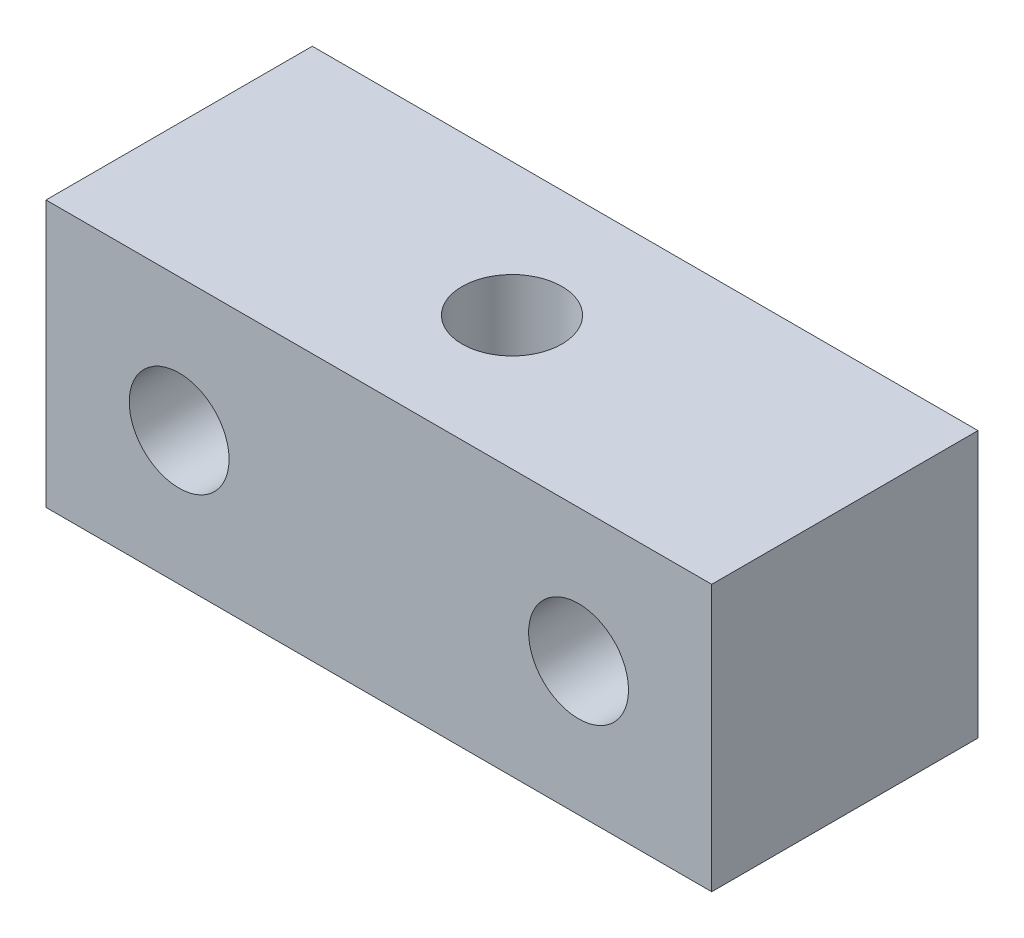
SolidWorks part; units mm, degrees
ref_plane "前视基准面" through (0, 0, 0) normal (0, 0, 1) x (1, 0, 0)
ref_plane "上视基准面" through (0, 0, 0) normal (0, 1, 0) x (1, 0, 0)
ref_plane "右视基准面" through (0, 0, 0) normal (1, 0, 0) x (0, 0, -1)
sketch "草图1" plane through (0, 0, 0) normal (1, 0, 0) x (0, 0, -1)
  line L1 (0, 0) -> (8, 0)
  line L2 (0, 0) -> (0, 8)
  line L3 (0, 8) -> (8, 8)
  line L4 (8, 0) -> (8, 8)
  dimension "D1" = 8
  dimension "D2" = 8
extrude "凸台-拉伸1" add sketch "草图1" along normal blind 20
sketch "草图3" plane through (0, 0, 0) normal (0, 0, 1) x (1, 0, 0)
  line L0 (10, 8) -> (10, 0) construction
  line L1 (20, 8) -> (0, 8) construction
  line L2 (20, 0) -> (0, 0) construction
  circle A0 centre (4, 4) radius 1.5
  circle A1 centre (16, 4) radius 1.5
  dimension "D4" = 3
  dimension "D1" = 12
  dimension "D2" = 6
  dimension "D3" = 4
extrude "切除-拉伸1" cut sketch "草图3" against normal through all
sketch "草图5" plane through (0, 8, 0) normal (0, 1, 0) x (1, 0, 0)
  line L0 (10, 8) -> (10, 0) construction
  line L1 (20, 8) -> (0, 8) construction
  line L2 (20, 0) -> (0, 0) construction
  line L3 (0, 4) -> (20, 4) construction
  line L4 (0, 8) -> (0, 0) construction
  line L5 (20, 8) -> (20, 0) construction
  circle A0 centre (10, 4) radius 1.5
  dimension "D1" = 3
extrude "切除-拉伸2" cut sketch "草图5" against normal through all
